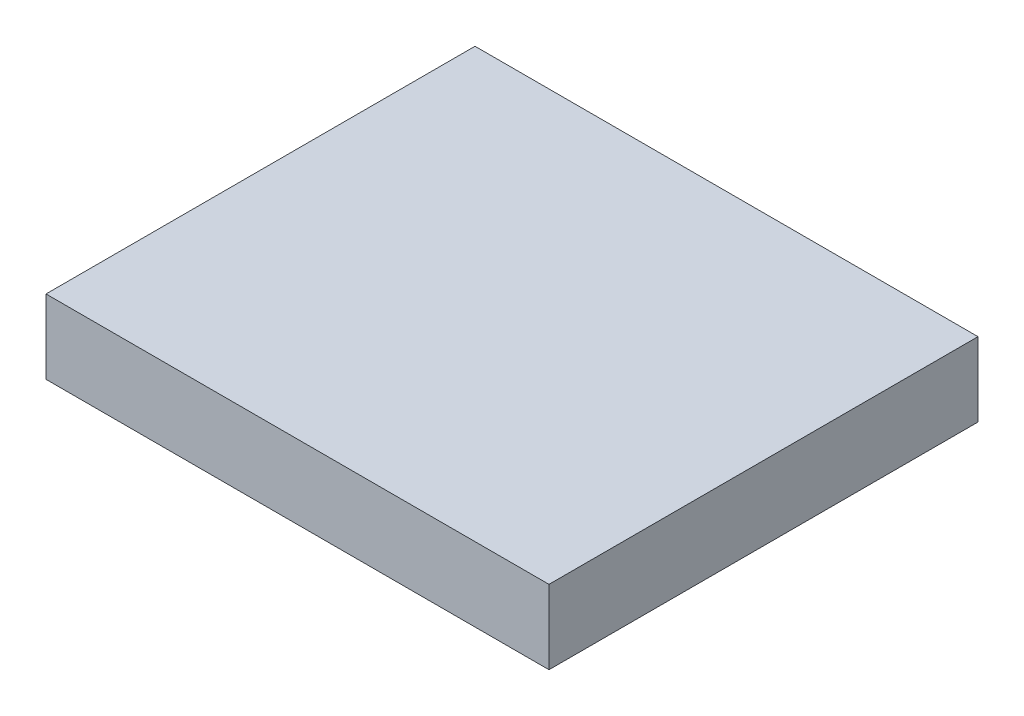
SolidWorks part; units mm, degrees
ref_plane "Front Plane" through (0, 0, 0) normal (0, 0, 1) x (1, 0, 0)
ref_plane "Top Plane" through (0, 0, 0) normal (0, 1, 0) x (1, 0, 0)
ref_plane "Right Plane" through (0, 0, 0) normal (1, 0, 0) x (0, 0, -1)
sketch "Sketch1" plane through (0, 0, 0) normal (0, 1, 0) x (1, 0, 0)
  line L1 (-17, 14.5) -> (17, 14.5)
  line L2 (-17, 14.5) -> (-17, -14.5)
  line L3 (-17, -14.5) -> (17, -14.5)
  line L4 (17, 14.5) -> (17, -14.5)
  line L5 (-17, 14.5) -> (17, -14.5) construction
  line L6 (-17, -14.5) -> (17, 14.5) construction
  point P0 (0, 0)
  dimension "D1" = 34
  dimension "D2" = 29
extrude "Boss-Extrude1" add sketch "Sketch1" along normal blind 5
